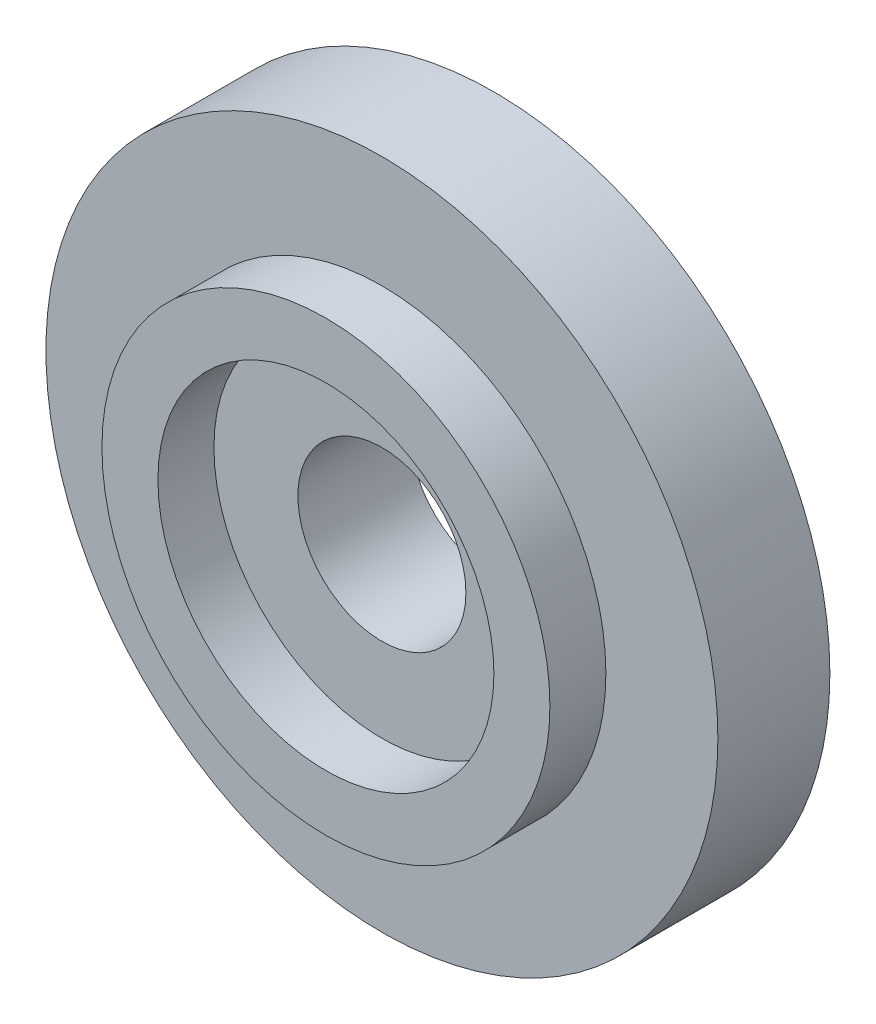
SolidWorks part; units mm, degrees
ref_plane "Front Plane" through (0, 0, 0) normal (0, 0, 1) x (1, 0, 0)
ref_plane "Top Plane" through (0, 0, 0) normal (0, 1, 0) x (1, 0, 0)
ref_plane "Right Plane" through (0, 0, 0) normal (1, 0, 0) x (0, 0, -1)
sketch "Sketch1" plane through (0, 0, 0) normal (0, 0, 1) x (1, 0, 0)
  circle A0 centre (0, 0) radius 6
  circle A1 centre (0, 0) radius 1.5
  dimension "D1" = 12
  dimension "D2" = 3
extrude "Boss-Extrude1" add sketch "Sketch1" along normal blind 2
sketch "Sketch2" plane through (0, 0, 2) normal (0, 0, 1) x (1, 0, 0)
  circle A0 centre (0, 0) radius 3
  circle A1 centre (0, 0) radius 4
extrude "Boss-Extrude2" add sketch "Sketch2" along normal blind 1
